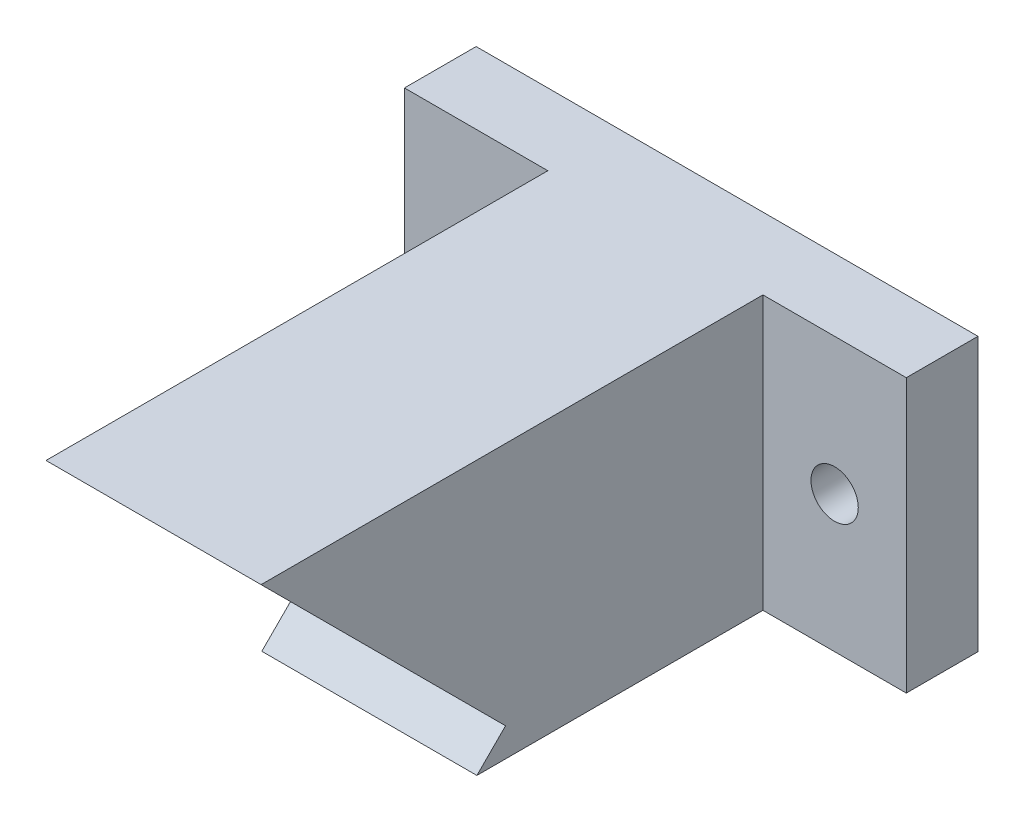
SolidWorks part; units mm, degrees
ref_plane "Front Plane" through (0, 0, 0) normal (0, 0, 1) x (1, 0, 0)
ref_plane "Top Plane" through (0, 0, 0) normal (0, 1, 0) x (1, 0, 0)
ref_plane "Right Plane" through (0, 0, 0) normal (1, 0, 0) x (0, 0, -1)
sketch "Sketch1" plane through (0, 0, 0) normal (0, 0, 1) x (1, 0, 0)
  line L1 (-7.5, -5) -> (7.5, -5)
  line L2 (-7.5, -5) -> (-7.5, 5)
  line L3 (-7.5, 5) -> (7.5, 5)
  line L4 (7.5, -5) -> (7.5, 5)
  line L5 (-7.5, -5) -> (7.5, 5) construction
  line L6 (-7.5, 5) -> (7.5, -5) construction
  point P0 (0, 0)
  dimension "D1" = 10
  dimension "D2" = 15
extrude "Boss-Extrude1" add sketch "Sketch1" along normal blind 40
sketch "Sketch2" plane through (7.5, 0, 0) normal (1, 0, 0) x (0, 0, -1)
  line L0 (-40, 5) -> (-40, -5)
  line L1 (-40, -5) -> (-30, -5)
  line L2 (-40, -5) -> (0, -5) construction
  line L3 (-30, -5) -> (-40, 5)
extrude "Cut-Extrude1" cut sketch "Sketch2" against normal blind 40
sketch "Sketch3" plane through (-7.5, 0, 0) normal (-1, 0, 0) x (0, 0, 1)
  line L0 (30, -5) -> (25.4774, -9.5226)
  line L1 (25.4774, -9.5226) -> (22.9493, -12.0507)
  line L2 (22.9493, -12.0507) -> (0, -12.0507)
  line L3 (0, -12.0507) -> (0, -5)
  line L5 (22.9493, -12.0507) -> (30, -5)
  line M1 (0, -5) -> (30, -5)
extrude "Boss-Extrude2" add sketch "Sketch3" against normal through all contours L3 L2 L1 L0 M1
sketch "Sketch4" plane through (0, -12.0507, 0) normal (0, -1, 0) x (-1, 0, 0)
  line L5 (-7.5, 0) -> (7.5, 0)
  line L6 (7.5, 0) -> (7.5, -24.5)
  line L7 (7.5, -22.9493) -> (7.5, -40) construction
  line L8 (7.5, -24.5) -> (-7.5, -24.5)
  line L9 (-7.5, -22.9493) -> (-7.5, -40) construction
  line L10 (-7.5, -24.5) -> (-7.5, 0)
extrude "Boss-Extrude3" add sketch "Sketch4" along normal blind 2
sketch "Sketch5" plane through (0, 0, 0) normal (0, 0, -1) x (-1, 0, 0)
  line L0 (7.5, -14.0507) -> (7.5, -12.0507)
  line L1 (7.5, 5) -> (7.5, -14.0507) construction
  line L2 (5.5, -12.0507) -> (-5.5, -12.0507)
  line L4 (-5.5, -12.0507) -> (5.5, -12.0507)
  line L6 (5.5, -12.0507) -> (5.5, 3)
  line L7 (-7.5, 5) -> (7.5, 5) construction
  line L8 (5.5, 5) -> (7.5, 5)
  line L9 (7.5, 5) -> (7.5, 3)
  line L10 (5.5, 3) -> (-5.5, 3)
  line L12 (-5.5, 3) -> (-5.5, -12.0507)
extrude "Cut-Extrude2" cut sketch "Sketch5" against normal through all contours L10 L12 L2 L6
sketch "Sketch6" plane through (0, 0, 0) normal (0, 0, -1) x (-1, 0, 0)
  line L0 (7.5, 5) -> (17.5, 5)
  line L1 (17.5, 5) -> (17.5, -14.0507)
  line L2 (17.5, -14.0507) -> (-7.5, -14.0507)
  line L3 (-7.5, -14.0507) -> (-17.5, -14.0507)
  line L4 (-17.5, -14.0507) -> (-17.5, 5)
  line L5 (-17.5, 5) -> (-7.5, 5)
  line L6 (-7.5, 5) -> (17.5, 5)
  line M1 (-5.5, 3) -> (5.5, 3)
  line M2 (5.5, 3) -> (5.5, -12.0507)
  line M3 (5.5, -12.0507) -> (-5.5, -12.0507)
  line M4 (-5.5, -12.0507) -> (-5.5, 3)
  line M5 (-7.5, 5) -> (-7.5, -14.0507)
  line M6 (-7.5, -14.0507) -> (7.5, -14.0507)
  line M7 (7.5, -14.0507) -> (7.5, 5)
  line M8 (7.5, 5) -> (-7.5, 5)
extrude "Boss-Extrude4" add sketch "Sketch6" against normal blind 5 contours L5 L4 L3 M5 | M1 M4 M3 M2 | L2 L1 L0 M7 | M8 M5 M6 M7 M4 M1 M2 M3
sketch "Sketch7" plane through (0, 0, 5) normal (0, 0, 1) x (1, 0, 0)
  line L0 (-12.5, 5) -> (-12.5, -14.0507)
  line L1 (-7.5, 5) -> (-17.5, 5) construction
  line L2 (-17.5, -14.0507) -> (-7.5, -14.0507) construction
  circle A0 centre (-12.5, -4.5254) radius 1.2766
sketch "Sketch8" plane through (0, 0, 5) normal (0, 0, 1) x (1, 0, 0)
  line L0 (12.5, 5) -> (12.5, -14.0507)
  line L1 (17.5, 5) -> (7.5, 5) construction
  line L2 (7.5, -14.0507) -> (17.5, -14.0507) construction
  circle A0 centre (12.5, -4.5254) radius 0.9508
hole_wizard "M4x0.7 Tapped Hole1" positions "Sketch9" profile "Sketch10" tap size "M4x0.7" standard "ANSI Metric" end condition through all
sketch "Sketch9" plane through (0, 0, 5) normal (0, 0, 1) x (1, 0, 0)
  point P0 (-12.5, -4.5254)
sketch "Sketch10" plane through (-12.5, -4.5254, 5) normal (1, 0, 0) x (0, -1, 0)
  line L0 (0, 0) -> (0, 5)
  line L1 (0, 5) -> (1.65, 5)
  line L2 (1.65, 5) -> (1.65, 0)
  line L5 (1.65, 0) -> (0, 0)
  line L11 (0, -6.35) -> (0, 107.95) construction
  dimension "Thru Tap Drill Dia." = 3.3
  dimension "Thru Tap Drill Depth" = 5
cosmetic thread "Hole Thread1" parameters "D2"=4
hole_wizard "M4x0.7 Tapped Hole2" positions "Sketch11" profile "Sketch12" tap size "M4x0.7" standard "ANSI Metric" end condition through all
sketch "Sketch11" plane through (0, 0, 5) normal (0, 0, 1) x (1, 0, 0)
  point P0 (12.5, -4.5254)
sketch "Sketch12" plane through (12.5, -4.5254, 5) normal (1, 0, 0) x (0, -1, 0)
  line L0 (0, 0) -> (0, 5)
  line L1 (0, 5) -> (1.65, 5)
  line L2 (1.65, 5) -> (1.65, 0)
  line L5 (1.65, 0) -> (0, 0)
  line L11 (0, -6.35) -> (0, 107.95) construction
  dimension "Thru Tap Drill Dia." = 3.3
  dimension "Thru Tap Drill Depth" = 5
cosmetic thread "Hole Thread2" parameters "D2"=4
sketch "Sketch13" plane through (-7.5, 0, 0) normal (-1, 0, 0) x (0, 0, 1)
  line L0 (22.9493, -12.0507) -> (22.9493, -14.0507)
  line L1 (24.5, -14.0507) -> (5, -14.0507) construction
  line L2 (22.9493, -14.0507) -> (22.9493, -12.0507)
  line L3 (22.9493, -12.0507) -> (24.5, -14.0507)
  line L4 (24.5, -14.0507) -> (24.5, -12.0507)
  line L5 (24.5, -12.0507) -> (22.9493, -12.0507)
  line M3 (24.5, -14.0507) -> (24.5, -12.0507)
  line M4 (24.5, -12.0507) -> (22.9493, -12.0507)
extrude "Cut-Extrude3" cut sketch "Sketch13" against normal through all contours L3 M4 M3
sketch "Sketch14" plane through (-7.5, 0, 0) normal (-1, 0, 0) x (0, 0, 1)
  line L0 (22.9493, -12.0507) -> (22.9493, -14.0507)
  line L1 (24.5, -14.0507) -> (5, -14.0507) construction
  line L2 (22.9493, -14.0507) -> (24.9493, -14.0507)
  line L3 (22.9493, -12.0507) -> (24.9493, -14.0507)
extrude "Boss-Extrude5" add sketch "Sketch14" against normal blind 15
